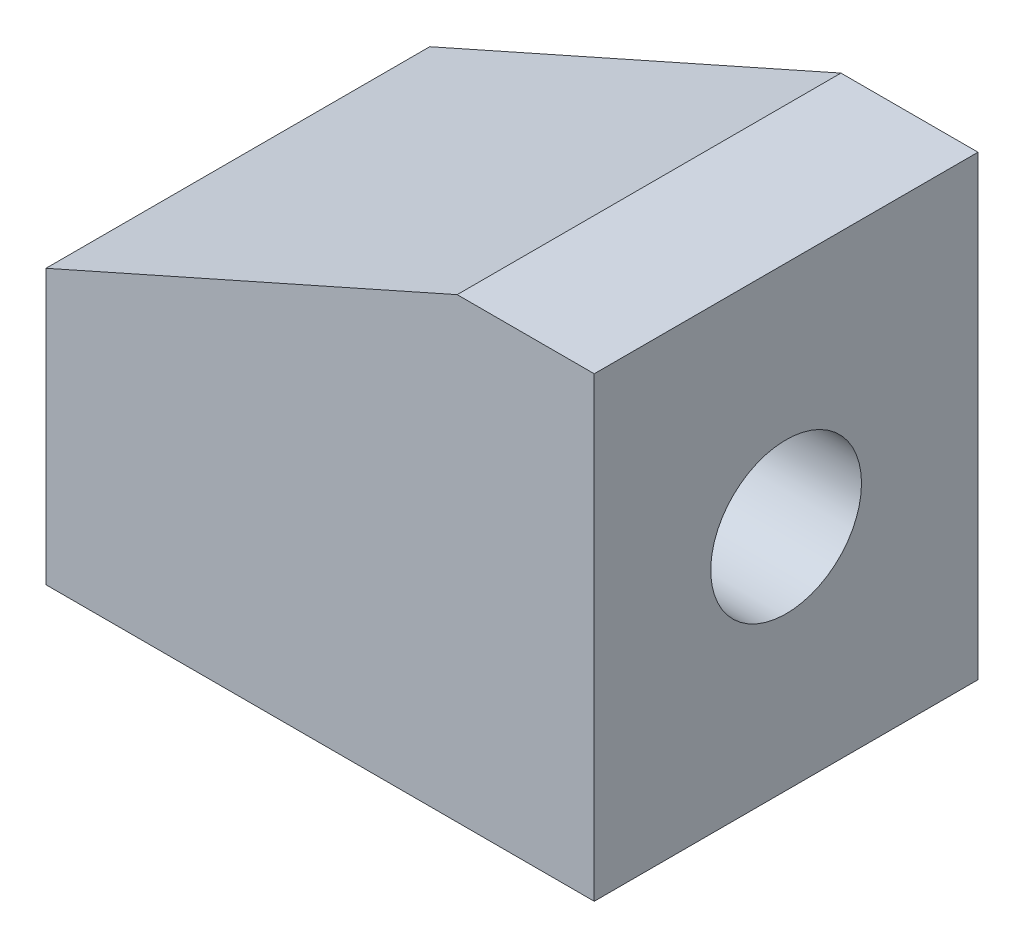
SolidWorks part; units mm, degrees
ref_plane "Front Plane" through (0, 0, 0) normal (0, 0, 1) x (1, 0, 0)
ref_plane "Top Plane" through (0, 0, 0) normal (0, 1, 0) x (1, 0, 0)
ref_plane "Right Plane" through (0, 0, 0) normal (1, 0, 0) x (0, 0, -1)
sketch "Sketch1" plane through (0, 0, 0) normal (0, 0, 1) x (1, 0, 0)
  line L0 (0, 0) -> (0, -30)
  line L1 (0, -30) -> (60, -30)
  line L2 (60, -30) -> (60, 20)
  line L3 (60, 20) -> (45, 20)
  line L4 (45, 20) -> (0, 0)
  dimension "D1" = 60
  dimension "D2" = 30
  dimension "D3" = 15
  dimension "D4" = 50
extrude "Boss-Extrude1" add sketch "Sketch1" along normal blind 42
sketch "Sketch2" plane through (60, 0, 0) normal (1, 0, 0) x (0, 0, -1)
  line L0 (-42, -30) -> (0, -30) construction
  line L1 (-42, -30) -> (0, -30)
  line L2 (-21, -30) -> (-21, -5)
  point P5 (-21, -5)
hole_wizard "M18x1.5 Tapped Hole1" positions "3DSketch1" profile "Sketch4" tap size "M18x1.5" standard "ISO"
sketch3d "3DSketch1"
  point P0 (60, -5, 21)
sketch "Sketch4" plane through (60, -5, 21) normal (0, 1, 0) x (0, 0, -1)
  line L0 (0, 0) -> (0, 48.4571)
  line L1 (0, 48.4571) -> (8.25, 43.5)
  line L2 (8.25, 43.5) -> (8.25, 0)
  line L5 (8.25, 0) -> (0, 0)
  line L10 (0, 48.4571) -> (-8.25, 43.5) construction
  line L11 (0, -6.35) -> (0, 107.95) construction
  dimension "Tap Drill Dia." = 16.5
  dimension "Tap Drill Depth" = 43.5
  dimension "Drill Angle" = 118
cosmetic thread "Hole Thread1" parameters "D1"=36, "D2"=18
